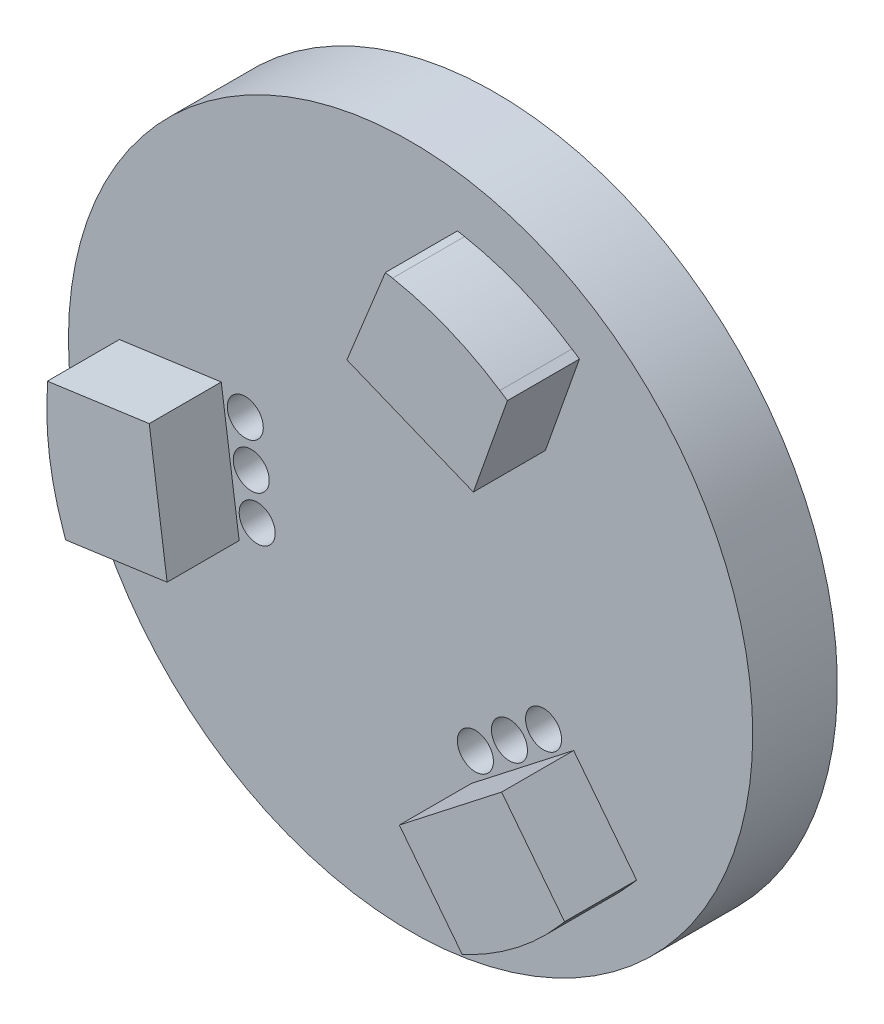
SolidWorks part; units mm, degrees
ref_plane "Front Plane" through (0, 0, 0) normal (0, 0, 1) x (1, 0, 0)
ref_plane "Top Plane" through (0, 0, 0) normal (0, 1, 0) x (1, 0, 0)
ref_plane "Right Plane" through (0, 0, 0) normal (1, 0, 0) x (0, 0, -1)
sketch "Sketch2" plane through (0, 0, 0) normal (0, 0, 1) x (1, 0, 0)
  circle A0 centre (0, 0) radius 9.5
  circle A1 centre (0, 0) radius 5.15
extrude "Boss-Extrude1" add sketch "Sketch2" along normal blind 3
sketch "Sketch3" plane through (0, 0, 3) normal (0, 0, 1) x (1, 0, 0)
  line L4 (6.144, -5.2784) -> (6.2755, -5.1253)
  line L5 (3.6163, -7.2479) -> (3.4357, -7.338)
  line L6 (-8.085, 0.6919) -> (-5.2563, 1.0856)
  line L7 (-5.2563, 1.0856) -> (-4.76, -2.48)
  line L8 (-4.76, -2.48) -> (-7.5764, -2.872)
  line L10 (-7.6432, -2.6816) -> (-7.5764, -2.872)
  line L12 (1.688, -5.0949) -> (3.4357, -7.338)
  line L13 (4.5277, -2.8823) -> (6.2755, -5.1253)
  line L14 (4.5277, -2.8823) -> (1.688, -5.0949)
  line L15 (3.7428, 3.9386) -> (4.6885, 6.6099)
  line L16 (0.2323, 5.3622) -> (1.3009, 7.9974)
  line L17 (0.2323, 5.3622) -> (3.7428, 3.9386)
  line L18 (-8.085, 0.4922) -> (-8.085, 0.6919)
  line L19 (4.4795, 6.7486) -> (4.6885, 6.6099)
  line L20 (1.4992, 7.96) -> (1.3009, 7.9974)
  arc A0 (6.144, -5.2784) -> (3.6163, -7.2479) centre (0, 0) cw
  arc A1 (1.4992, 7.96) -> (4.4795, 6.7486) centre (0, 0) cw
  arc A3 (-7.6432, -2.6816) -> (-8.085, 0.4922) centre (0, 0) cw
extrude "Boss-Extrude2" add sketch "Sketch3" along normal blind 2
sketch "Sketch4" plane through (0, 0, 0) normal (0, 0, -1) x (-1, 0, 0)
  circle A0 centre (0, 0) radius 5.15
extrude "Boss-Extrude3" add sketch "Sketch4" against normal up to surface (3 mm away) up to face at (9.5, 0, 3)
sketch "Sketch5" plane through (0, 0, 3) normal (0, 0, 1) x (1, 0, 0)
  line L0 (0, 0) -> (3.1078, -3.9886) construction
  line L1 (4.5277, -2.8823) -> (1.688, -5.0949) construction
  line L2 (2.7454, -3.5234) -> (1.7988, -4.261) construction
  line L3 (0, 0) -> (5.7487, 0.8003) construction
  line L4 (0, 0) -> (-1.1071, -2.7298) construction
  circle A0 centre (2.7454, -3.5234) radius 0.5
  circle A1 centre (1.7988, -4.261) radius 0.5
  circle A2 centre (3.6919, -2.7858) radius 0.5
  circle A3 centre (0.5666, 4.5902) radius 0.5
  circle A4 centre (1.6787, 4.1393) radius 0.5
  circle A5 centre (2.7907, 3.6883) radius 0.5
  circle A6 centre (-4.2586, -1.8044) radius 0.5
  circle A7 centre (-4.424, -0.6159) radius 0.5
  circle A8 centre (-4.5895, 0.5727) radius 0.5
  dimension "D2" = 1
  dimension "D3" = 1
  dimension "D1" = 1.2
  dimension "D4" = 60
  dimension "D5" = 60
extrude "Cut-Extrude1" cut sketch "Sketch5" against normal through all
sketch "Sketch6" plane through (0, 0, 0) normal (0, 0, -1) x (-1, 0, 0)
  circle A2 centre (0, 0) radius 9.5
  circle A3 centre (0, 0) radius 9.5
  dimension "D1" = 0
extrude "Cut-Extrude2" cut sketch "Sketch6" against normal blind 0.65
